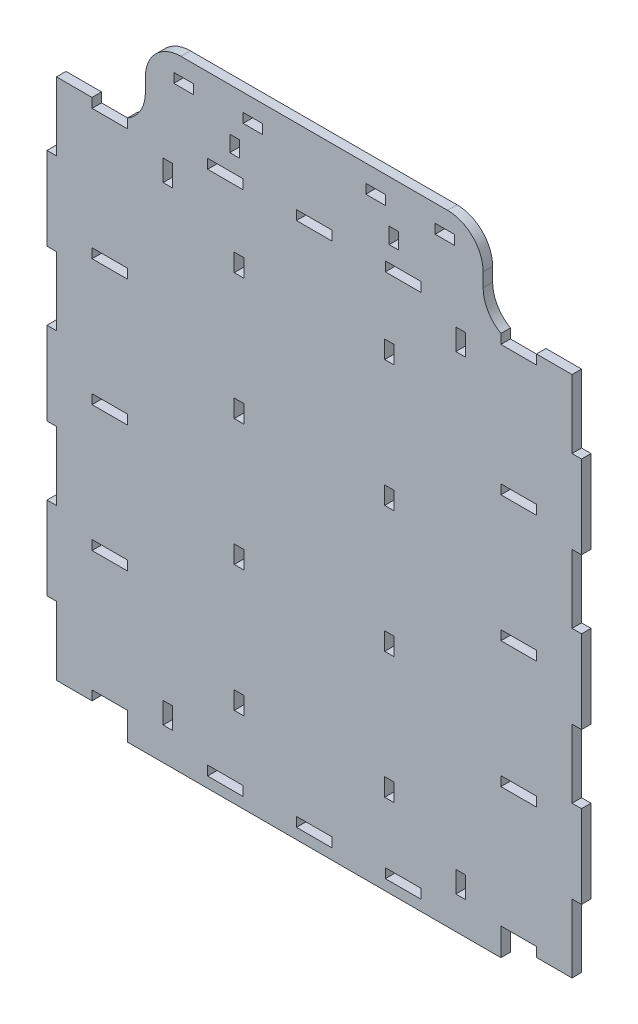
SolidWorks part; units mm, degrees
ref_plane "Front Plane" through (0, 0, 0) normal (0, 0, 1) x (1, 0, 0)
ref_plane "Top Plane" through (0, 0, 0) normal (0, 1, 0) x (1, 0, 0)
ref_plane "Right Plane" through (0, 0, 0) normal (1, 0, 0) x (0, 0, -1)
sketch "Model" plane through (0, 0, 0) normal (0, 0, 1) x (1, 0, 0)
  line L0 (295.35, 304.1082) -> (295.35, 265.6082)
  line L1 (295.35, 265.6082) -> (300.7, 265.6082)
  line L2 (300.7, 265.6082) -> (300.7, 218.9415)
  line L3 (300.7, 218.9415) -> (295.35, 218.9415)
  line L4 (295.35, 218.9415) -> (295.35, 180.4415)
  line L5 (295.35, 180.4415) -> (300.7, 180.4415)
  line L6 (300.7, 180.4415) -> (300.7, 133.7748)
  line L7 (300.7, 133.7748) -> (295.35, 133.7748)
  line L8 (295.35, 133.7748) -> (295.35, 95.2748)
  line L9 (295.35, 95.2748) -> (300.7, 95.2748)
  line L10 (300.7, 95.2748) -> (300.7, 48.6082)
  line L11 (300.7, 48.6082) -> (295.35, 48.6082)
  line L12 (295.35, 48.6082) -> (295.35, 10.1082)
  line L13 (295.35, 10.1082) -> (275.35, 10.1082)
  line L14 (275.35, 10.1082) -> (275.35, 15.4582)
  line L15 (275.35, 15.4582) -> (255.35, 15.4582)
  line L16 (255.35, 15.4582) -> (255.35, 0)
  line L17 (245.35, 329.1082) -> (245.35, 321.4287)
  line L18 (255.35, 304.1082) -> (255.35, 298.7582)
  line L19 (255.35, 298.7582) -> (275.35, 298.7582)
  line L20 (275.35, 298.7582) -> (275.35, 304.1082)
  line L21 (275.35, 304.1082) -> (295.35, 304.1082)
  line L22 (229.35, 333.95) -> (218.35, 333.95)
  line L23 (229.35, 339.3) -> (229.35, 333.95)
  line L24 (218.35, 339.3) -> (229.35, 339.3)
  line L25 (218.35, 333.95) -> (218.35, 339.3)
  line L26 (190.35, 333.95) -> (179.35, 333.95)
  line L27 (190.35, 339.3) -> (190.35, 333.95)
  line L28 (105.35, 268.7262) -> (110.7, 268.7262)
  line L29 (105.35, 258.7262) -> (105.35, 268.7262)
  line L30 (110.7, 258.7262) -> (105.35, 258.7262)
  line L31 (110.7, 268.7262) -> (110.7, 258.7262)
  line L32 (105.35, 197.6475) -> (110.7, 197.6475)
  line L33 (105.35, 187.6475) -> (105.35, 197.6475)
  line L34 (110.7, 187.6475) -> (105.35, 187.6475)
  line L35 (110.7, 197.6475) -> (110.7, 187.6475)
  line L36 (105.35, 126.5688) -> (110.7, 126.5688)
  line L37 (105.35, 116.5688) -> (105.35, 126.5688)
  line L38 (110.7, 116.5688) -> (105.35, 116.5688)
  line L39 (110.7, 126.5688) -> (110.7, 116.5688)
  line L40 (105.35, 55.4902) -> (110.7, 55.4902)
  line L41 (105.35, 45.4902) -> (105.35, 55.4902)
  line L42 (110.7, 45.4902) -> (105.35, 45.4902)
  line L43 (110.7, 55.4902) -> (110.7, 45.4902)
  line L44 (25.35, 225.5118) -> (25.35, 230.8618)
  line L45 (45.35, 225.5118) -> (25.35, 225.5118)
  line L46 (45.35, 230.8618) -> (45.35, 225.5118)
  line L47 (25.35, 230.8618) -> (45.35, 230.8618)
  line L48 (25.35, 154.4332) -> (25.35, 159.7832)
  line L49 (45.35, 154.4332) -> (25.35, 154.4332)
  line L50 (45.35, 159.7832) -> (45.35, 154.4332)
  line L51 (25.35, 159.7832) -> (45.35, 159.7832)
  line L52 (25.35, 83.3545) -> (25.35, 88.7045)
  line L53 (45.35, 83.3545) -> (25.35, 83.3545)
  line L54 (45.35, 88.7045) -> (45.35, 83.3545)
  line L55 (25.35, 88.7045) -> (45.35, 88.7045)
  line L56 (102.85, 315.95) -> (108.2, 315.95)
  line L57 (108.2, 315.95) -> (108.2, 324.95)
  line L58 (108.2, 324.95) -> (102.85, 324.95)
  line L59 (102.85, 324.95) -> (102.85, 315.95)
  line L60 (70.7, 294.6) -> (65.35, 294.6)
  line L61 (65.35, 294.6) -> (65.35, 282.6)
  line L62 (65.35, 282.6) -> (70.7, 282.6)
  line L63 (70.7, 282.6) -> (70.7, 294.6)
  line L64 (179.35, 339.3) -> (190.35, 339.3)
  line L65 (179.35, 333.95) -> (179.35, 339.3)
  line L66 (160.35, 11.35) -> (160.35, 6)
  line L67 (210.35, 6) -> (190.35, 6)
  line L68 (110.35, 301.6) -> (110.35, 306.95)
  line L69 (110.35, 306.95) -> (90.35, 306.95)
  line L70 (90.35, 306.95) -> (90.35, 301.6)
  line L71 (90.35, 301.6) -> (110.35, 301.6)
  line L72 (210.35, 11.35) -> (210.35, 6)
  line L73 (160.35, 306.95) -> (140.35, 306.95)
  line L74 (140.35, 306.95) -> (140.35, 301.6)
  line L75 (140.35, 301.6) -> (160.35, 301.6)
  line L76 (190.35, 11.35) -> (210.35, 11.35)
  line L77 (190.35, 6) -> (190.35, 11.35)
  line L78 (235.35, 30.35) -> (235.35, 18.35)
  line L79 (230, 30.35) -> (235.35, 30.35)
  line L80 (65.35, 18.35) -> (70.7, 18.35)
  line L81 (70.7, 18.35) -> (70.7, 30.35)
  line L82 (70.7, 30.35) -> (65.35, 30.35)
  line L83 (65.35, 30.35) -> (65.35, 18.35)
  line L84 (110.35, 6) -> (110.35, 11.35)
  line L85 (110.35, 11.35) -> (90.35, 11.35)
  line L86 (90.35, 11.35) -> (90.35, 6)
  line L87 (90.35, 6) -> (110.35, 6)
  line L88 (230, 18.35) -> (230, 30.35)
  line L89 (160.35, 11.35) -> (140.35, 11.35)
  line L90 (140.35, 11.35) -> (140.35, 6)
  line L91 (140.35, 6) -> (160.35, 6)
  line L92 (235.35, 18.35) -> (230, 18.35)
  line L93 (160.35, 306.95) -> (160.35, 301.6)
  line L94 (210.35, 301.6) -> (190.35, 301.6)
  line L95 (210.35, 306.95) -> (210.35, 301.6)
  line L96 (190.35, 306.95) -> (210.35, 306.95)
  line L97 (190.35, 301.6) -> (190.35, 306.95)
  line L98 (230, 282.6) -> (230, 294.6)
  line L99 (235.35, 282.6) -> (230, 282.6)
  line L100 (121.35, 333.95) -> (121.35, 339.3)
  line L101 (121.35, 339.3) -> (110.35, 339.3)
  line L102 (110.35, 339.3) -> (110.35, 333.95)
  line L103 (110.35, 333.95) -> (121.35, 333.95)
  line L104 (82.35, 333.95) -> (82.35, 339.3)
  line L105 (82.35, 339.3) -> (71.35, 339.3)
  line L106 (71.35, 339.3) -> (71.35, 333.95)
  line L107 (71.35, 333.95) -> (82.35, 333.95)
  line L108 (235.35, 294.6) -> (235.35, 282.6)
  line L109 (230, 294.6) -> (235.35, 294.6)
  line L110 (197.85, 324.95) -> (197.85, 315.95)
  line L111 (192.5, 324.95) -> (197.85, 324.95)
  line L112 (192.5, 315.95) -> (192.5, 324.95)
  line L113 (197.85, 315.95) -> (192.5, 315.95)
  line L114 (275.35, 88.7045) -> (255.35, 88.7045)
  line L115 (255.35, 88.7045) -> (255.35, 83.3545)
  line L116 (255.35, 83.3545) -> (275.35, 83.3545)
  line L117 (275.35, 83.3545) -> (275.35, 88.7045)
  line L118 (275.35, 159.7832) -> (255.35, 159.7832)
  line L119 (255.35, 159.7832) -> (255.35, 154.4332)
  line L120 (25.35, 304.1082) -> (5.35, 304.1082)
  line L121 (25.35, 298.7582) -> (25.35, 304.1082)
  line L122 (45.35, 298.7582) -> (25.35, 298.7582)
  line L123 (45.35, 304.1082) -> (45.35, 298.7582)
  line L124 (55.35, 329.1082) -> (55.35, 321.4287)
  line L125 (225.35, 349.1082) -> (75.35, 349.1082)
  line L126 (255.35, 154.4332) -> (275.35, 154.4332)
  line L127 (275.35, 154.4332) -> (275.35, 159.7832)
  line L128 (275.35, 230.8618) -> (255.35, 230.8618)
  line L129 (255.35, 230.8618) -> (255.35, 225.5118)
  line L130 (255.35, 225.5118) -> (275.35, 225.5118)
  line L131 (275.35, 225.5118) -> (275.35, 230.8618)
  line L132 (190, 55.4902) -> (190, 45.4902)
  line L133 (190, 45.4902) -> (195.35, 45.4902)
  line L134 (195.35, 45.4902) -> (195.35, 55.4902)
  line L135 (195.35, 55.4902) -> (190, 55.4902)
  line L136 (190, 126.5688) -> (190, 116.5688)
  line L137 (190, 116.5688) -> (195.35, 116.5688)
  line L138 (195.35, 116.5688) -> (195.35, 126.5688)
  line L139 (195.35, 126.5688) -> (190, 126.5688)
  line L140 (190, 197.6475) -> (190, 187.6475)
  line L141 (190, 187.6475) -> (195.35, 187.6475)
  line L142 (195.35, 187.6475) -> (195.35, 197.6475)
  line L143 (195.35, 197.6475) -> (190, 197.6475)
  line L144 (190, 268.7262) -> (190, 258.7262)
  line L145 (190, 258.7262) -> (195.35, 258.7262)
  line L146 (195.35, 258.7262) -> (195.35, 268.7262)
  line L147 (195.35, 268.7262) -> (190, 268.7262)
  line L148 (45.35, 0) -> (255.35, 0)
  line L149 (45.35, 15.4582) -> (45.35, 0)
  line L150 (25.35, 15.4582) -> (45.35, 15.4582)
  line L151 (25.35, 10.1082) -> (25.35, 15.4582)
  line L152 (5.35, 10.1082) -> (25.35, 10.1082)
  line L153 (5.35, 48.6082) -> (5.35, 10.1082)
  line L154 (0, 48.6082) -> (5.35, 48.6082)
  line L155 (0, 95.2748) -> (0, 48.6082)
  line L156 (5.35, 95.2748) -> (0, 95.2748)
  line L157 (5.35, 133.7748) -> (5.35, 95.2748)
  line L158 (0, 133.7748) -> (5.35, 133.7748)
  line L159 (0, 180.4415) -> (0, 133.7748)
  line L160 (5.35, 180.4415) -> (0, 180.4415)
  line L161 (5.35, 218.9415) -> (5.35, 180.4415)
  line L162 (0, 218.9415) -> (5.35, 218.9415)
  line L163 (0, 265.6082) -> (0, 218.9415)
  line L164 (5.35, 265.6082) -> (0, 265.6082)
  line L165 (5.35, 304.1082) -> (5.35, 265.6082)
  line L166 (150.35, 0) -> (150.35, 378.2011) construction
  arc A0 (225.35, 349.1082) -> (245.35, 329.1082) centre (225.35, 329.1082) cw
  arc A1 (255.35, 304.1082) -> (245.35, 321.4287) centre (265.35, 321.4287) cw
  arc A2 (45.35, 304.1082) -> (55.35, 321.4287) centre (35.35, 321.4287) ccw
  arc A3 (75.35, 349.1082) -> (55.35, 329.1082) centre (75.35, 329.1082) ccw
  point P35 (150.35, 349.1082)
  point P89 (150.35, 6)
  point P90 (150.35, 11.35)
  point P109 (150.35, 301.6)
  point P110 (150.35, 306.95)
  dimension "D25" = 20
  dimension "D27" = 20
  dimension "D1" = 20
  dimension "D2" = 5.35
  dimension "D3" = 105
  dimension "D4" = 20
  dimension "D5" = 20
  dimension "D6" = 5.35
  dimension "D7" = 5.35
  dimension "D8" = 15.4582
  dimension "D9" = 38.5
  dimension "D10" = 46.6667
  dimension "D11" = 5.35
  dimension "D12" = 38.5
  dimension "D13" = 5.35
  dimension "D14" = 46.6667
  dimension "D15" = 5.35
  dimension "D16" = 38.5
  dimension "D17" = 5.35
  dimension "D18" = 46.6667
  dimension "D19" = 5.35
  dimension "D20" = 38.5
  dimension "D21" = 20
  dimension "D22" = 5.35
  dimension "D23" = 20
  dimension "D24" = 5.35
  dimension "D26" = 7.6795
  dimension "D28" = 75
  dimension "D29" = 6
  dimension "D30" = 5.35
  dimension "D31" = 10
  dimension "D32" = 6
  dimension "D33" = 12
  dimension "D34" = 5.35
  dimension "D35" = 40
  dimension "D36" = 2.8918
  dimension "D37" = 79.65
  dimension "D38" = 10
  dimension "D39" = 5.35
  dimension "D40" = 39.65
  dimension "D41" = 3.118
  dimension "D42" = 5.35
  dimension "D43" = 20
  dimension "D44" = 105
  dimension "D45" = 83.3545
  dimension "D46" = 5.35
  dimension "D47" = 10
  dimension "D48" = 20
  dimension "D49" = 5.35
  dimension "D50" = 10
  dimension "D51" = 5.35
  dimension "D52" = 5.35
  dimension "D53" = 20
  dimension "D54" = 5.35
  dimension "D55" = 10
  dimension "D56" = 10
  dimension "D57" = 5.35
  dimension "D58" = 12
  dimension "D59" = 5.35
  dimension "D60" = 20
  dimension "D61" = 5.35
  dimension "D62" = 9
  dimension "D63" = 5.35
  dimension "D64" = 11
  dimension "D65" = 5.35
  dimension "D66" = 11
  dimension "D67" = 5.35
  dimension "D68" = 9.8082
  dimension "D69" = 29
  dimension "D70" = 9.8082
  dimension "D71" = 68
  dimension "D72" = 42.15
  dimension "D73" = 24.1582
  dimension "D74" = 42.1582
  dimension "D75" = 40
  dimension "D76" = 2.8418
  dimension "D77" = 39.65
  dimension "D78" = 21.294
  dimension "D79" = 105
  dimension "D80" = 20.6583
  dimension "D81" = 6.5703
  dimension "D82" = 7.206
  dimension "D83" = 39.65
  dimension "D84" = 105
  dimension "D85" = 39.65
  dimension "D86" = 6.882
  dimension "D87" = 79.65
  dimension "D88" = 16.9918
extrude "Boss-Extrude1" add sketch "Model" along normal blind 5.35
